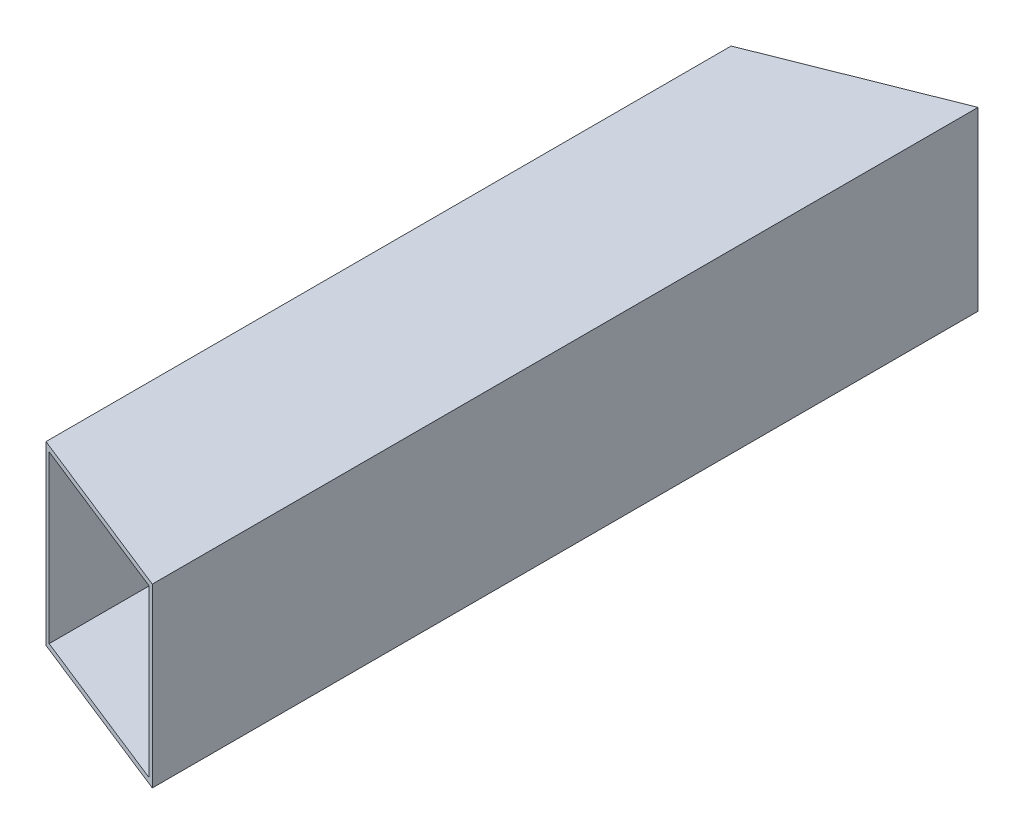
SolidWorks part; units mm, degrees
ref_plane "Plano frontal" through (0, 0, 0) normal (0, 0, 1) x (1, 0, 0)
ref_plane "Plano superior" through (0, 0, 0) normal (0, 1, 0) x (1, 0, 0)
ref_plane "Plano direito" through (0, 0, 0) normal (1, 0, 0) x (0, 0, -1)
sketch "Esboço1" plane through (0, 0, 0) normal (0, 0, 1) x (1, 0, 0)
  line L1 (-15.9452, -15.9452) -> (15.9452, -15.9452)
  line L2 (-15.9452, -15.9452) -> (-15.9452, 15.9452)
  line L3 (-15.9452, 15.9452) -> (15.9452, 15.9452)
  line L4 (15.9452, -15.9452) -> (15.9452, 15.9452)
  line L5 (-15.9452, -15.9452) -> (15.9452, 15.9452) construction
  line L6 (-15.9452, 15.9452) -> (15.9452, -15.9452) construction
  line L7 (-15, -15) -> (15, -15)
  line L8 (-15, -15) -> (-15, 15)
  line L9 (-15, 15) -> (15, 15)
  line L10 (15, -15) -> (15, 15)
  line L11 (-15, -15) -> (15, 15) construction
  line L12 (-15, 15) -> (15, -15) construction
  point P0 (0, 0)
  point P6 (0, 0)
extrude "Ressalto-extrusão1" add sketch "Esboço1" along normal blind 149.1169
ref_plane "Plano1" through (0, 0, 74.5584) normal (0, 0, -1) x (-1, 0, 0)
sketch "Esboço3" plane through (0, 15.9452, 0) normal (0, 1, 0) x (1, 0, 0)
  line L0 (15.9452, 0) -> (-15.9452, -12.6926)
  line L2 (-15.9452, -149.1169) -> (-15.9452, 0) construction
extrude "Corte-extrusão1" cut sketch "Esboço3" against normal through all and the other way through all
mirror "Espelhar5" about plane through (0, 0, 74.5584) normal (0, 0, -1) of "Corte-extrusão1"
